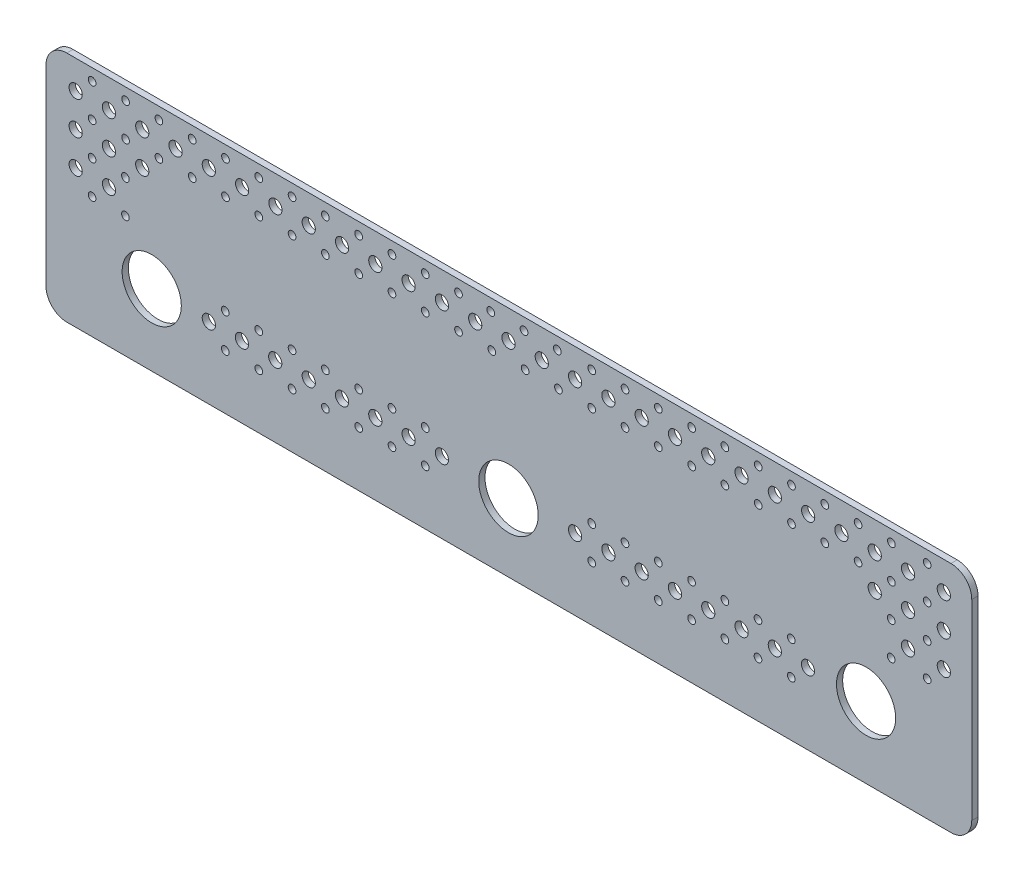
SolidWorks part; units mm, degrees
ref_plane "Front" through (0, 0, 0) normal (0, 0, 1) x (1, 0, 0)
ref_plane "Top" through (0, 0, 0) normal (0, 1, 0) x (1, 0, 0)
ref_plane "Right" through (0, 0, 0) normal (1, 0, 0) x (0, 0, -1)
sketch "Sketch1" plane through (0, 0, 0) normal (0, 0, 1) x (1, 0, 0)
  line L1 (-435.1498, 91.0845) -> (-10.2738, 91.0845)
  line L2 (-445.1498, 81.0845) -> (-445.1498, -10.9155)
  line L3 (-435.1498, -20.9155) -> (-10.2738, -20.9155)
  line L4 (-0.2738, 81.0845) -> (-0.2738, -10.9155)
  circle A0 centre (-394.3498, 13.3845) radius 14.225
  circle A1 centre (-51.0738, 13.3845) radius 14.225
  circle A11 centre (-222.8998, 11.8845) radius 14.3
  circle A20 centre (-30.8998, 61.3845) radius 3.18
  circle A21 centre (-414.8998, 61.3845) radius 3.18
  circle A23 centre (-286.8998, 13.3845) radius 3.18
  arc A24 (-10.2738, -20.9155) -> (-0.2738, -10.9155) centre (-10.2738, -10.9155) ccw
  arc A25 (-435.1498, -20.9155) -> (-445.1498, -10.9155) centre (-435.1498, -10.9155) cw
  arc A26 (-435.1498, 91.0845) -> (-445.1498, 81.0845) centre (-435.1498, 81.0845) ccw
  arc A27 (-10.2738, 91.0845) -> (-0.2738, 81.0845) centre (-10.2738, 81.0845) cw
  circle A28 centre (-302.8998, 13.3845) radius 3.18
  circle A29 centre (-318.8998, 13.3845) radius 3.18
  circle A30 centre (-270.8998, 13.3845) radius 3.18
  circle A31 centre (-254.8998, 13.3845) radius 3.18
  circle A45 centre (-310.8998, 5.3845) radius 1.85
  circle A46 centre (-294.8998, 5.3845) radius 1.85
  circle A47 centre (-278.8998, 5.3845) radius 1.85
  circle A48 centre (-262.8998, 5.3845) radius 1.85
  circle A49 centre (-310.8998, 21.3845) radius 1.85
  circle A50 centre (-294.8998, 21.3845) radius 1.85
  circle A51 centre (-278.8998, 21.3845) radius 1.85
  circle A52 centre (-262.8998, 21.3845) radius 1.85
  circle A53 centre (-158.8998, 13.3845) radius 3.18
  circle A54 centre (-174.8998, 13.3845) radius 3.18
  circle A55 centre (-190.8998, 13.3845) radius 3.18
  circle A56 centre (-142.8998, 13.3845) radius 3.18
  circle A57 centre (-126.8998, 13.3845) radius 3.18
  circle A58 centre (-182.8998, 5.3845) radius 1.85
  circle A59 centre (-166.8998, 5.3845) radius 1.85
  circle A60 centre (-150.8998, 5.3845) radius 1.85
  circle A61 centre (-134.8998, 5.3845) radius 1.85
  circle A62 centre (-182.8998, 21.3845) radius 1.85
  circle A63 centre (-166.8998, 21.3845) radius 1.85
  circle A64 centre (-150.8998, 21.3845) radius 1.85
  circle A65 centre (-134.8998, 21.3845) radius 1.85
  circle A66 centre (-318.8998, 77.3845) radius 3.18
  circle A67 centre (-334.8998, 77.3845) radius 3.18
  circle A68 centre (-334.8998, 77.3845) radius 3.18
  circle A69 centre (-302.8998, 77.3845) radius 3.18
  circle A70 centre (-286.8998, 77.3845) radius 3.18
  circle A71 centre (-310.8998, 69.3845) radius 1.85
  circle A72 centre (-294.8998, 69.3845) radius 1.85
  circle A73 centre (-278.8998, 69.3845) radius 1.85
  circle A74 centre (-262.8998, 69.3845) radius 1.85
  circle A75 centre (-310.8998, 85.3845) radius 1.85
  circle A76 centre (-294.8998, 85.3845) radius 1.85
  circle A77 centre (-278.8998, 85.3845) radius 1.85
  circle A78 centre (-262.8998, 85.3845) radius 1.85
  circle A79 centre (-270.8998, 77.3845) radius 3.18
  circle A80 centre (-142.8998, 77.3845) radius 3.18
  circle A81 centre (-158.8998, 77.3845) radius 3.18
  circle A82 centre (-174.8998, 77.3845) radius 3.18
  circle A83 centre (-126.8998, 77.3845) radius 3.18
  circle A84 centre (-110.8998, 77.3845) radius 3.18
  circle A85 centre (-182.8998, 69.3845) radius 1.85
  circle A86 centre (-166.8998, 69.3845) radius 1.85
  circle A87 centre (-150.8998, 69.3845) radius 1.85
  circle A88 centre (-134.8998, 69.3845) radius 1.85
  circle A89 centre (-182.8998, 85.3845) radius 1.85
  circle A90 centre (-166.8998, 85.3845) radius 1.85
  circle A91 centre (-150.8998, 85.3845) radius 1.85
  circle A92 centre (-134.8998, 85.3845) radius 1.85
  circle A94 centre (-222.8998, 77.3845) radius 3.18
  circle A95 centre (-238.8998, 77.3845) radius 3.18
  circle A96 centre (-254.8998, 77.3845) radius 3.18
  circle A97 centre (-206.8998, 77.3845) radius 3.18
  circle A98 centre (-190.8998, 77.3845) radius 3.18
  circle A99 centre (-246.8998, 69.3845) radius 1.85
  circle A100 centre (-230.8998, 69.3845) radius 1.85
  circle A101 centre (-214.8998, 69.3845) radius 1.85
  circle A102 centre (-198.8998, 69.3845) radius 1.85
  circle A103 centre (-246.8998, 85.3845) radius 1.85
  circle A104 centre (-231.4272, 85.3845) radius 1.85
  circle A105 centre (-215.4272, 85.3845) radius 1.85
  circle A106 centre (-199.4272, 85.3845) radius 1.85
  circle A107 centre (-398.8998, 77.3845) radius 3.18
  circle A108 centre (-414.8998, 77.3845) radius 3.18
  circle A109 centre (-382.8998, 77.3845) radius 3.18
  circle A110 centre (-366.8998, 77.3845) radius 3.18
  circle A111 centre (-390.8998, 69.3845) radius 1.85
  circle A112 centre (-374.8998, 69.3845) radius 1.85
  circle A113 centre (-358.8998, 69.3845) radius 1.85
  circle A114 centre (-342.8998, 69.3845) radius 1.85
  circle A115 centre (-390.8998, 85.3845) radius 1.85
  circle A116 centre (-374.8998, 85.3845) radius 1.85
  circle A117 centre (-358.8998, 85.3845) radius 1.85
  circle A118 centre (-342.8998, 85.3845) radius 1.85
  circle A119 centre (-350.8998, 77.3845) radius 3.18
  circle A120 centre (-78.8998, 77.3845) radius 3.18
  circle A121 centre (-94.8998, 77.3845) radius 3.18
  circle A122 centre (-62.8998, 77.3845) radius 3.18
  circle A123 centre (-46.8998, 77.3845) radius 3.18
  circle A124 centre (-86.8998, 69.3845) radius 1.85
  circle A125 centre (-70.8998, 69.3845) radius 1.85
  circle A126 centre (-54.8998, 69.3845) radius 1.85
  circle A127 centre (-38.8998, 69.3845) radius 1.85
  circle A128 centre (-86.8998, 85.3845) radius 1.85
  circle A129 centre (-70.8998, 85.3845) radius 1.85
  circle A130 centre (-54.8998, 85.3845) radius 1.85
  circle A131 centre (-38.8998, 85.3845) radius 1.85
  circle A132 centre (-30.8998, 77.3845) radius 3.18
  circle A133 centre (-430.8998, 77.3845) radius 3.18
  circle A134 centre (-430.8998, 61.3845) radius 3.18
  circle A135 centre (-422.9957, 69.3845) radius 1.85
  circle A136 centre (-406.8998, 69.3845) radius 1.85
  circle A137 centre (-422.9957, 85.3845) radius 1.85
  circle A138 centre (-406.8998, 85.3845) radius 1.85
  circle A139 centre (-13.7008, 61.3845) radius 3.18
  circle A140 centre (-21.7008, 69.3845) radius 1.85
  circle A141 centre (-21.7008, 85.3845) radius 1.85
  circle A142 centre (-13.7008, 77.3845) radius 3.18
  circle A143 centre (-118.8998, 69.3845) radius 1.85
  circle A144 centre (-102.8998, 69.3845) radius 1.85
  circle A145 centre (-118.8998, 85.3845) radius 1.85
  circle A146 centre (-102.8998, 85.3845) radius 1.85
  circle A147 centre (-326.8998, 69.3845) radius 1.85
  circle A148 centre (-326.8998, 85.3845) radius 1.85
  circle A149 centre (-334.9957, 13.3845) radius 3.18
  circle A150 centre (-350.9957, 13.3845) radius 3.18
  circle A151 centre (-366.8998, 13.3845) radius 3.18
  circle A152 centre (-358.9957, 5.3845) radius 1.85
  circle A153 centre (-342.8998, 5.3845) radius 1.85
  circle A154 centre (-326.8998, 5.3845) radius 1.85
  circle A155 centre (-358.9957, 21.7191) radius 1.85
  circle A156 centre (-342.8998, 21.7191) radius 1.85
  circle A157 centre (-326.8998, 21.7191) radius 1.85
  circle A158 centre (-110.8998, 13.3845) radius 3.18
  circle A159 centre (-94.8998, 13.3845) radius 3.18
  circle A160 centre (-78.9957, 13.3845) radius 3.18
  circle A161 centre (-118.8998, 5.3845) radius 1.85
  circle A162 centre (-102.9957, 5.3845) radius 1.85
  circle A163 centre (-86.9957, 5.3845) radius 1.85
  circle A164 centre (-118.8998, 21.3845) radius 1.85
  circle A165 centre (-102.9957, 21.3845) radius 1.85
  circle A166 centre (-86.9957, 21.3845) radius 1.85
  circle A167 centre (-422.9957, 37.3845) radius 1.85
  circle A168 centre (-406.9957, 37.3845) radius 1.85
  circle A169 centre (-422.9957, 53.3845) radius 1.85
  circle A170 centre (-406.9957, 53.3845) radius 1.85
  circle A171 centre (-38.9957, 37.3845) radius 1.85
  circle A172 centre (-38.9957, 53.3845) radius 1.85
  circle A173 centre (-21.7008, 37.3845) radius 1.85
  circle A174 centre (-21.7008, 53.3845) radius 1.85
  circle A175 centre (-398.8998, 61.3845) radius 3.18
  circle A176 centre (-414.8998, 45.3845) radius 3.18
  circle A177 centre (-430.8998, 45.3845) radius 3.18
  circle A178 centre (-46.8998, 61.3845) radius 3.18
  circle A179 centre (-30.8998, 45.3845) radius 3.18
  circle A180 centre (-13.7008, 45.3845) radius 3.18
  point P45 (-0.2738, -20.9155)
  point P52 (-0.2738, 91.0845)
  dimension "D2" = 50.8
  dimension "D4" = 50.8
  dimension "D6" = 8
  dimension "D8" = 8
  dimension "D12" = 222.25
  dimension "D13" = 8
  dimension "D14" = 16
  dimension "D15" = 16
  dimension "D16" = 16
  dimension "D17" = 16
  dimension "D21" = 16
  dimension "D23" = 16
  dimension "D27" = 10
  dimension "D28" = 10
  dimension "D29" = 10
  dimension "D30" = 10
  dimension "D24" = 16
  dimension "D1" = 112
  dimension "D3" = 34.3
  dimension "D5" = 34.3
  dimension "D7" = 8
  dimension "D9" = 16
  dimension "D10" = 16
  dimension "D11" = 8
  dimension "D18" = 16
  dimension "D19" = 16
  dimension "D20" = 16
  dimension "D22" = 16
  dimension "D25" = 16
  dimension "D26" = 32.8
  dimension "D31" = 16
  dimension "D32" = 16
  dimension "D33" = 16
  dimension "D34" = 16
  dimension "D35" = 8
  dimension "D36" = 16
  dimension "D37" = 8
  dimension "D38" = 16
  dimension "D39" = 16
  dimension "D40" = 16
  dimension "D41" = 8
  dimension "D42" = 16
  dimension "D43" = 16
  dimension "D44" = 16
  dimension "D45" = 16
  dimension "D46" = 16
  dimension "D47" = 16
  dimension "D48" = 16
  dimension "D49" = 64
  dimension "D50" = 16
  dimension "D51" = 16
  dimension "D52" = 16
  dimension "D53" = 16
  dimension "D54" = 16
  dimension "D55" = 32
  dimension "D56" = 16
  dimension "D57" = 16
  dimension "D58" = 16
  dimension "D59" = 16
  dimension "D60" = 13.7
  dimension "D61" = 8
  dimension "D62" = 16
  dimension "D63" = 16
  dimension "D64" = 8
  dimension "D65" = 16
  dimension "D66" = 16
  dimension "D67" = 16
  dimension "D68" = 16
  dimension "D69" = 16
  dimension "D70" = 16
  dimension "D71" = 16
  dimension "D72" = 16
  dimension "D73" = 16
  dimension "D74" = 16
  dimension "D75" = 16
  dimension "D76" = 16
  dimension "D77" = 16
  dimension "D78" = 16
  dimension "D79" = 16
  dimension "D80" = 16
  dimension "D81" = 8
  dimension "D82" = 16
  dimension "D83" = 16
  dimension "D84" = 16
  dimension "D85" = 16
extrude "Boss-Extrude1" add sketch "Sketch1" along normal blind 3
